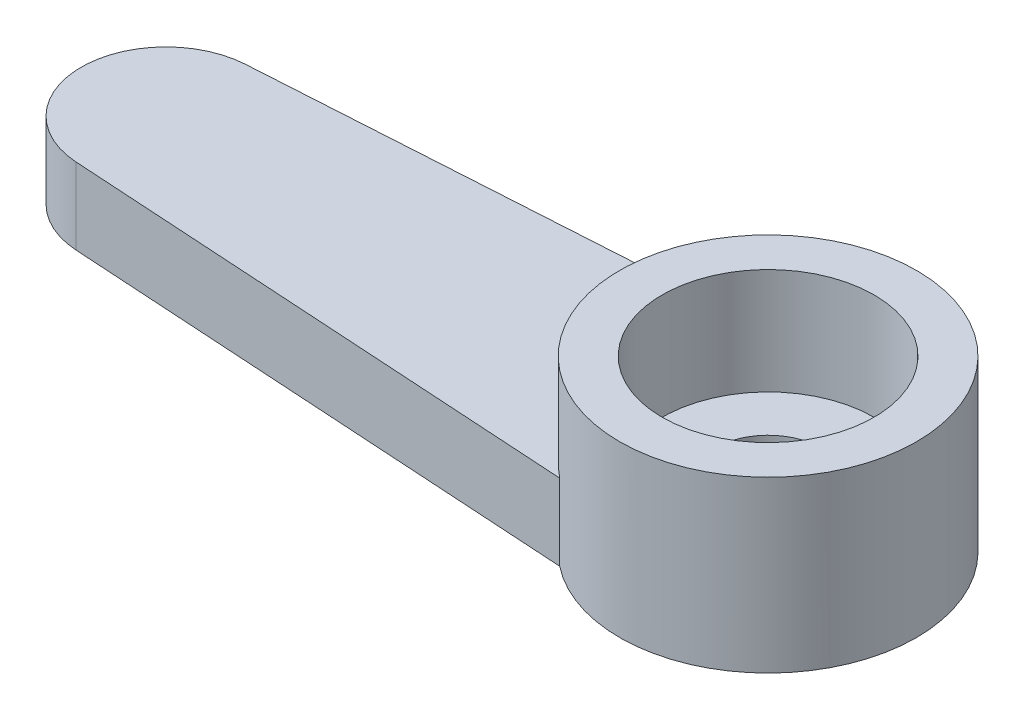
SolidWorks part; units mm, degrees
ref_plane "Front Plane" through (0, 0, 0) normal (0, 0, 1) x (1, 0, 0)
ref_plane "Top Plane" through (0, 0, 0) normal (0, 1, 0) x (1, 0, 0)
ref_plane "Right Plane" through (0, 0, 0) normal (1, 0, 0) x (0, 0, -1)
sketch "Sketch1" plane through (0, 0, 0) normal (0, 1, 0) x (1, 0, 0)
  circle A0 centre (0, 0) radius 2.5
  circle A1 centre (0, 0) radius 3.5
  dimension "D1" = 5
  dimension "D2" = 7
extrude "Boss-Extrude1" add sketch "Sketch1" along normal blind 4
sketch "Sketch2" plane through (0, 0, 0) normal (0, 1, 0) x (1, 0, 0)
  line L0 (3.5, 0) -> (-16.2, 0) construction
  line L1 (-2.1651, 2.75) -> (-14.3238, 1.9962)
  line L2 (-2.1651, -2.75) -> (-14.3238, -1.9962)
  circle A0 centre (0, 0) radius 3.5 construction
  arc A1 (-14.3238, 1.9962) -> (-14.3238, -1.9962) centre (-14.2, 0) ccw
  arc A2 (-2.1651, 2.75) -> (-2.1651, -2.75) centre (0, 0) ccw
  point P8 (0, 0)
  point P9 (-13.1266, 0)
  point P12 (-12.8289, 2.3506)
  dimension "D3" = 4
  dimension "D1" = 19.7
  dimension "D2" = 5.5
extrude "Boss-Extrude2" add sketch "Sketch2" along normal blind 1.8
sketch "Sketch3" plane through (0, 0, 0) normal (0, 1, 0) x (1, 0, 0)
  circle A0 centre (0, 0) radius 2.5 construction
  circle A1 centre (0, 0) radius 2.5
  circle A2 centre (0, 0) radius 1.25
  dimension "D1" = 2.5
extrude "Boss-Extrude3" add sketch "Sketch3" along normal blind 1.5
